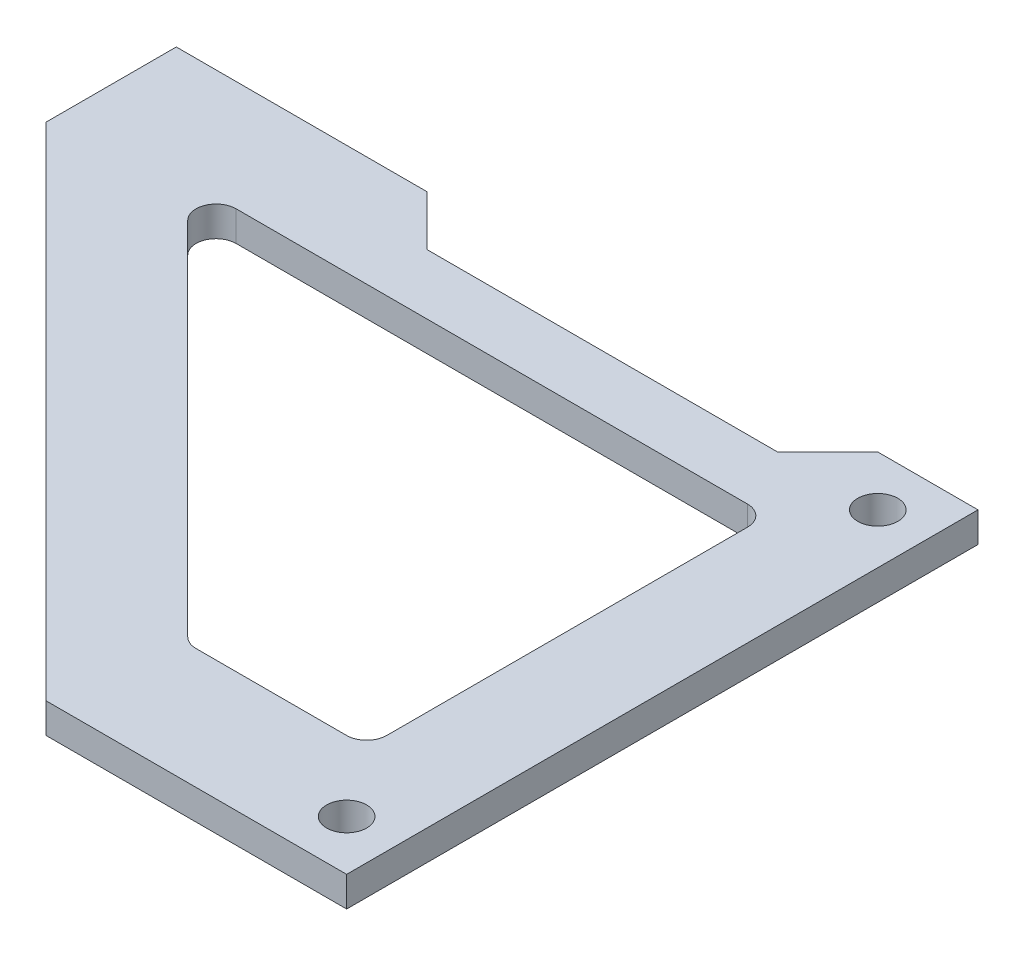
SolidWorks part; units mm, degrees
ref_plane "前视基准面" through (0, 0, 0) normal (0, 0, 1) x (1, 0, 0)
ref_plane "上视基准面" through (0, 0, 0) normal (0, 1, 0) x (1, 0, 0)
ref_plane "右视基准面" through (0, 0, 0) normal (1, 0, 0) x (0, 0, -1)
other "Configuration Table"
sketch "草图1" plane through (0, 0, 0) normal (0, 1, 0) x (1, 0, 0)
  line L0 (-65, 26.5) -> (-65, -26.5) construction
  line L1 (-140, 31.5) -> (140, 31.5)
  line L2 (-140, 31.5) -> (-140, -31.5)
  line L3 (-140, -31.5) -> (140, -31.5)
  line L4 (140, 31.5) -> (140, -31.5)
  line L5 (-140, 31.5) -> (140, -31.5) construction
  line L6 (-140, -31.5) -> (140, 31.5) construction
  line L7 (-65, 0) -> (0, 0) construction
  line L8 (0, 0) -> (0, 31.5) construction
  circle A0 centre (-65, 26.5) radius 2
  circle A1 centre (-65, -26.5) radius 2
  circle A2 centre (65, -26.5) radius 2
  circle A3 centre (65, 26.5) radius 2
  point P0 (0, 0)
  dimension "D1" = 4
  dimension "D2" = 53
  dimension "D3" = 63
  dimension "D4" = 65
  dimension "D5" = 280
extrude "凸台-拉伸1" add sketch "草图1" along normal blind 3
sketch "草图2" plane through (0, 3, 0) normal (0, 1, 0) x (1, 0, 0)
  line L0 (-140, 18.5) -> (-140, -31.5)
  line L1 (-140, 31.5) -> (-140, -31.5) construction
  line L2 (-140, -31.5) -> (-90, -31.5)
  line L3 (-140, -31.5) -> (140, -31.5) construction
  line L4 (-90, -31.5) -> (-140, 18.5)
  line L5 (0, 0) -> (0, -31.5) construction
  line L6 (90, -31.5) -> (140, 18.5)
  line L7 (140, -31.5) -> (90, -31.5)
  line L8 (140, 18.5) -> (140, -31.5)
  dimension "D1" = 50
  dimension "D2" = 50
extrude "切除-拉伸1" cut sketch "草图2" against normal blind 3
sketch "草图3" plane through (0, 3, 0) normal (0, 1, 0) x (1, 0, 0)
  line L0 (140, 31.5) -> (-140, 31.5) construction
  line L1 (-60, 31.5) -> (140, 31.5)
  line L2 (-60, 31.5) -> (-60, -31.5)
  line L3 (-60, -31.5) -> (140, -31.5)
  line L4 (140, 31.5) -> (140, -31.5)
  line L5 (140, 18.5) -> (140, 31.5) construction
  line L6 (-90, -31.5) -> (90, -31.5) construction
  line L7 (-65, 26.5) -> (-65, -26.5) construction
  dimension "D1" = 5
extrude "切除-拉伸2" cut sketch "草图3" against normal blind 10
sketch "草图4" plane through (0, 3, 0) normal (0, 1, 0) x (1, 0, 0)
  line L0 (-115, 31.5) -> (-110, 26.5)
  line L1 (-60, 31.5) -> (-140, 31.5) construction
  line L2 (-110, 26.5) -> (-75, 26.5)
  line L3 (-75, 26.5) -> (-70, 31.5)
  line L4 (-115, 31.5) -> (-70, 31.5)
  line L5 (-60, 31.5) -> (-60, -31.5) construction
  line L6 (-140, 31.5) -> (-140, 18.5) construction
  point P4 (-77.1018, 21.5)
  point P7 (-74.1944, 25.5)
  point P12 (-119.4125, 25.5)
  dimension "D1" = 5
  dimension "D2" = 45
  dimension "D3" = 10
  dimension "D4" = 25
  dimension "D5" = 45
extrude "切除-拉伸3" cut sketch "草图4" against normal blind 10
sketch "草图5" plane through (0, 3, 0) normal (0, 1, 0) x (1, 0, 0)
  line L3 (-127.8579, 20.5) -> (-70, 20.5)
  line L4 (-70, 20.5) -> (-70, -19.5)
  line L5 (-70, -19.5) -> (-87.8579, -19.5)
  line L6 (-87.8579, -19.5) -> (-127.8579, 20.5)
  line L8 (-110, 26.5) -> (-75, 26.5) construction
  line L9 (-90, -31.5) -> (-60, -31.5) construction
  line L10 (-60, 31.5) -> (-60, -31.5) construction
  line L13 (-90, -31.5) -> (-140, 18.5) construction
  point P2 (-69.6967, 21.8937)
  point P6 (-85.7585, -25.2297)
  point P13 (-122.8581, 13.5732)
  point P16 (-125.0076, 20.5)
  point P17 (-121.096, 13.7382)
  point P18 (-127.8967, 20.5)
  point P19 (-127.0964, 20.5388)
  dimension "D2" = 6
  dimension "D3" = 12
  dimension "D4" = 10
  dimension "D5" = 10
extrude "切除-拉伸4" cut sketch "草图5" against normal blind 10
fillet "圆角1" radius 2 4 edges at (-87.8579, 1.5, 19.5) (-70, 1.5, -20.5) (-70, 1.5, 19.5) (-127.8579, 1.5, -20.5)
